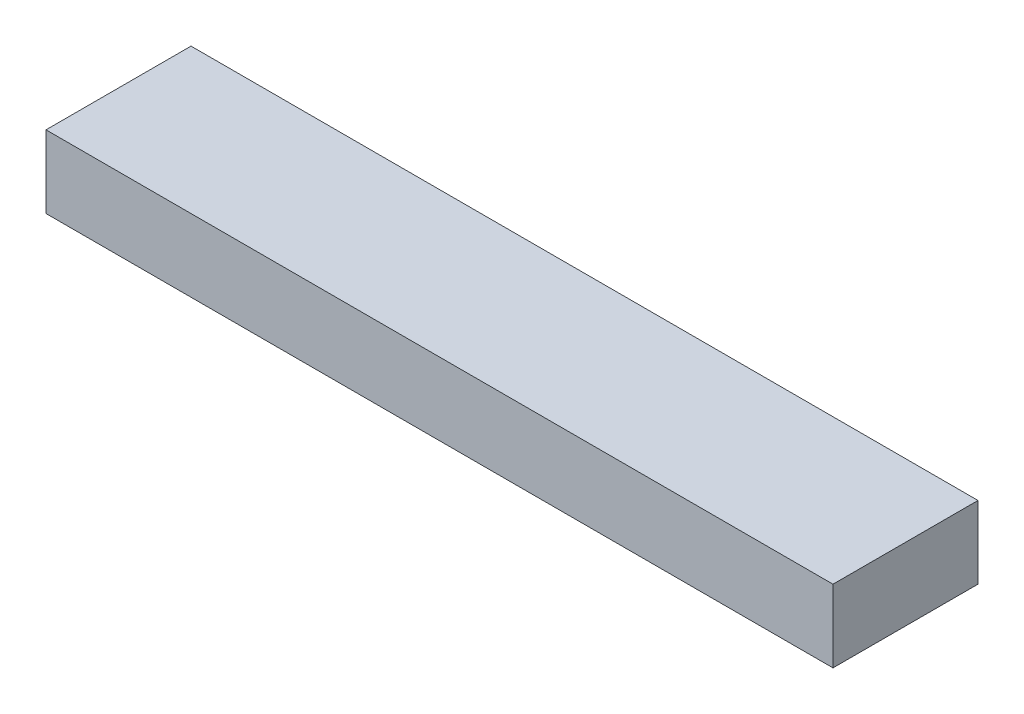
SolidWorks part; units mm, degrees
ref_plane "Front Plane" through (0, 0, 0) normal (0, 0, 1) x (1, 0, 0)
ref_plane "Top Plane" through (0, 0, 0) normal (0, 1, 0) x (1, 0, 0)
ref_plane "Right Plane" through (0, 0, 0) normal (1, 0, 0) x (0, 0, -1)
sketch "Sketch1" plane through (0, 0, 0) normal (0, 0, 1) x (1, 0, 0)
  line L1 (-108.54, 10) -> (108.54, 10)
  line L2 (-108.54, 10) -> (-108.54, -10)
  line L3 (-108.54, -10) -> (108.54, -10)
  line L4 (108.54, 10) -> (108.54, -10)
  line L5 (-108.54, 10) -> (108.54, -10) construction
  line L6 (-108.54, -10) -> (108.54, 10) construction
  point P0 (0, 0)
  dimension "D1" = 217.08
  dimension "D2" = 20
extrude "Boss-Extrude1" add sketch "Sketch1" along normal blind 40
sketch "Sketch2" plane through (0, 0, 0) normal (0, 0, 1) x (1, 0, 0)
  line L0 (-108.54, 0) -> (108.54, 0) construction
  line L1 (-108.54, 10) -> (-108.54, -10) construction
  line L2 (108.54, -10) -> (108.54, 10) construction
  circle A0 centre (-56.04, 0) radius 5
  circle A1 centre (56.04, 0) radius 5
  point P10 (0, 0)
  point P11 (0, 0)
  point P12 (0, 0)
  point P13 (0, 0)
  point P14 (0, 0)
  point P15 (0, 0)
  point P16 (0, 0)
  point P17 (0, 0)
  point P18 (0, 0)
  point P19 (0, 0)
  point P20 (0, 0)
  point P22 (0, 0)
  point P23 (0, 0)
  point P24 (0, 0)
  point P25 (0, 0)
  dimension "D1" = 10
  dimension "D2" = 10
  dimension "D3" = 52.5
  dimension "D4" = 52.5
extrude "Cut-Extrude3" cut sketch "Sketch2" along normal blind 35
